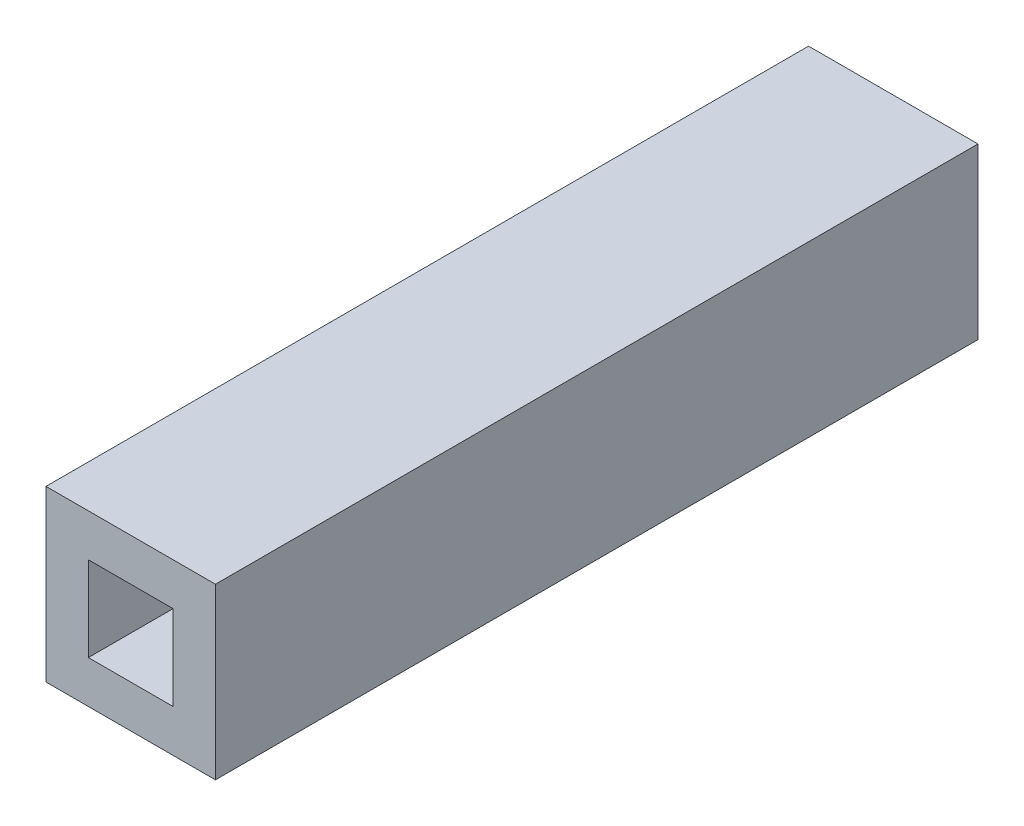
SolidWorks part; units mm, degrees
material "6063-O"
ref_plane "Front Plane" through (0, 0, 0) normal (0, 0, 1) x (1, 0, 0)
ref_plane "Top Plane" through (0, 0, 0) normal (0, 1, 0) x (1, 0, 0)
ref_plane "Right Plane" through (0, 0, 0) normal (1, 0, 0) x (0, 0, -1)
sketch "Sketch1" plane through (0, 0, 0) normal (0, 0, 1) x (1, 0, 0)
  line L1 (-10, -10) -> (10, -10)
  line L2 (-10, -10) -> (-10, 10)
  line L3 (-10, 10) -> (10, 10)
  line L4 (10, -10) -> (10, 10)
  line L5 (-10, -10) -> (10, 10) construction
  line L6 (-10, 10) -> (10, -10) construction
  point P0 (0, 0)
  dimension "D1" = 20
extrude "Extrude-Thin1" add sketch "Sketch1" along normal blind 90 thin thin type one direction reverse wall 5
